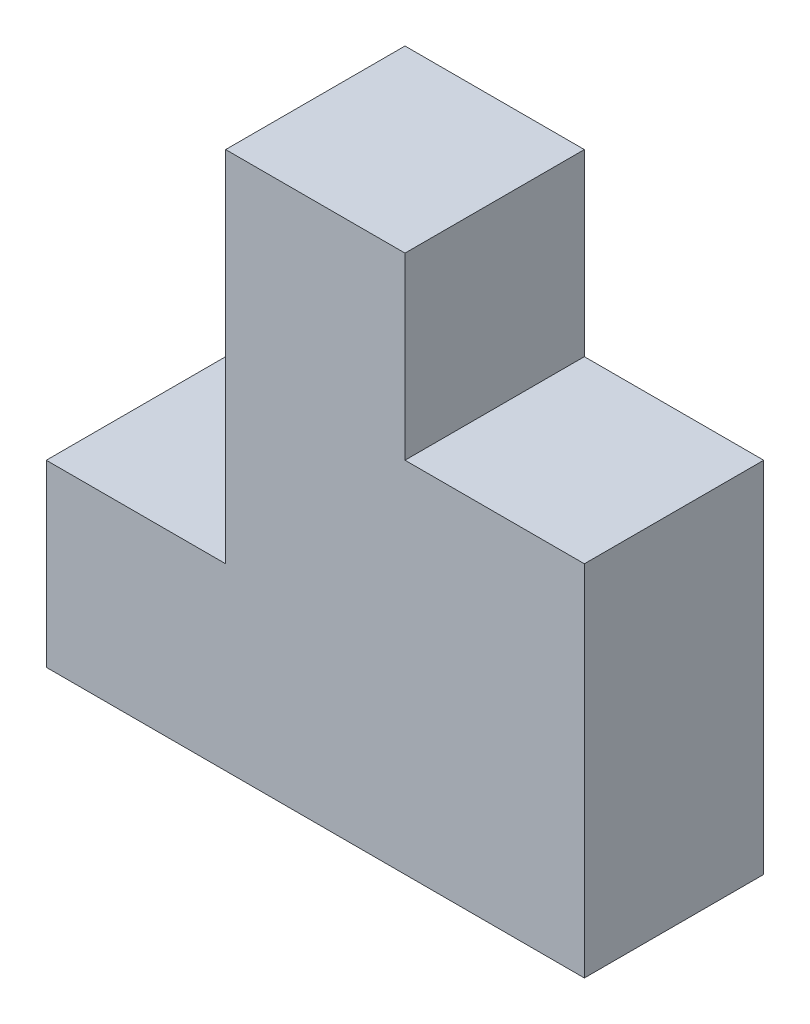
SolidWorks part; units mm, degrees
ref_plane "Front Plane" through (0, 0, 0) normal (0, 0, 1) x (1, 0, 0)
ref_plane "Top Plane" through (0, 0, 0) normal (0, 1, 0) x (1, 0, 0)
ref_plane "Right Plane" through (0, 0, 0) normal (1, 0, 0) x (0, 0, -1)
sketch "Sketch1" plane through (0, 0, 0) normal (0, 0, 1) x (1, 0, 0)
  line L0 (0, 0) -> (57.15, 0)
  line L1 (57.15, 0) -> (57.15, 38.1)
  line L2 (57.15, 38.1) -> (38.1, 38.1)
  line L3 (38.1, 38.1) -> (38.1, 57.15)
  line L4 (38.1, 57.15) -> (19.05, 57.15)
  line L5 (19.05, 57.15) -> (19.05, 19.05)
  line L7 (19.05, 19.05) -> (0, 19.05)
  line L8 (0, 19.05) -> (0, 0)
  point P5 (25.3148, 20.9678)
  dimension "D1" = 19.05
  dimension "D2" = 38.1
  dimension "D3" = 19.05
  dimension "D4" = 57.15
  dimension "D5" = 38.1
  dimension "D6" = 19.05
extrude "Boss-Extrude1" add sketch "Sketch1" along normal blind 19.05
